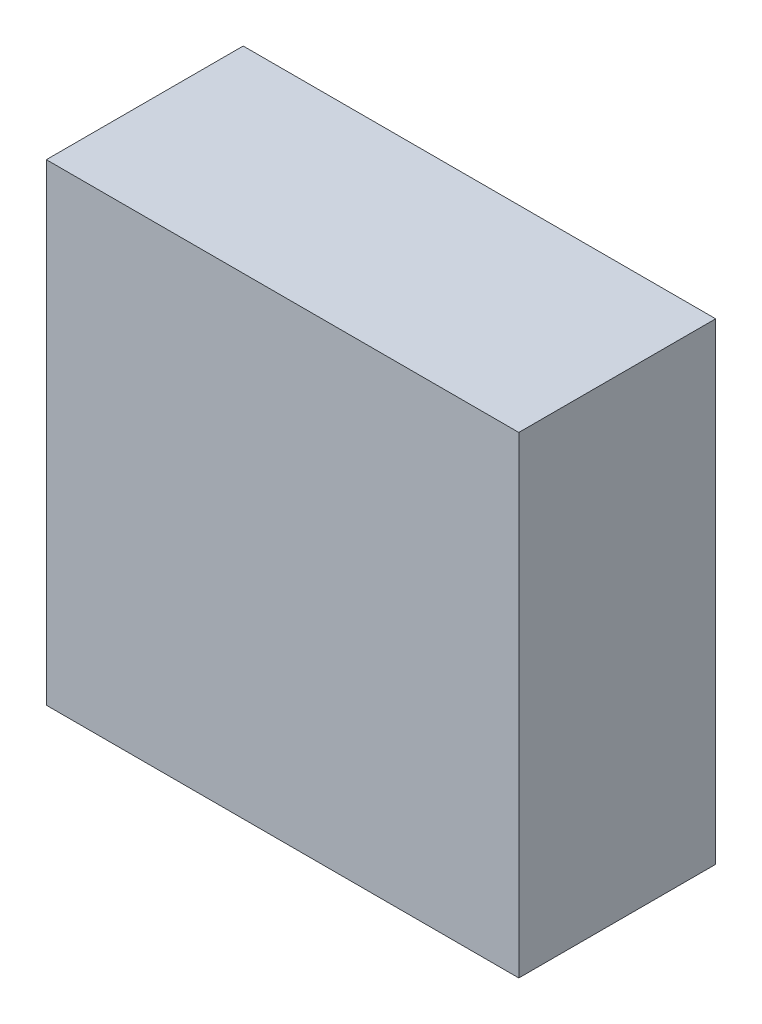
SolidWorks part; units mm, degrees
material "Custom Plastic"
ref_plane "X-Y Datum" through (0, 0, 0) normal (0, 0, 1) x (1, 0, 0)
ref_plane "X-Z Datum" through (0, 0, 0) normal (0, 1, 0) x (1, 0, 0)
ref_plane "Y-Z Datum" through (0, 0, 0) normal (1, 0, 0) x (0, 0, -1)
sketch "Sketch1" plane through (0, 0, 0) normal (0, 0, 1) x (1, 0, 0)
  line L1 (0, 0) -> (60, 0)
  line L2 (0, 0) -> (0, 60)
  line L3 (0, 60) -> (60, 60)
  line L4 (60, 0) -> (60, 60)
extrude "Boss-Extrude1" add sketch "Sketch1" along normal blind 25
